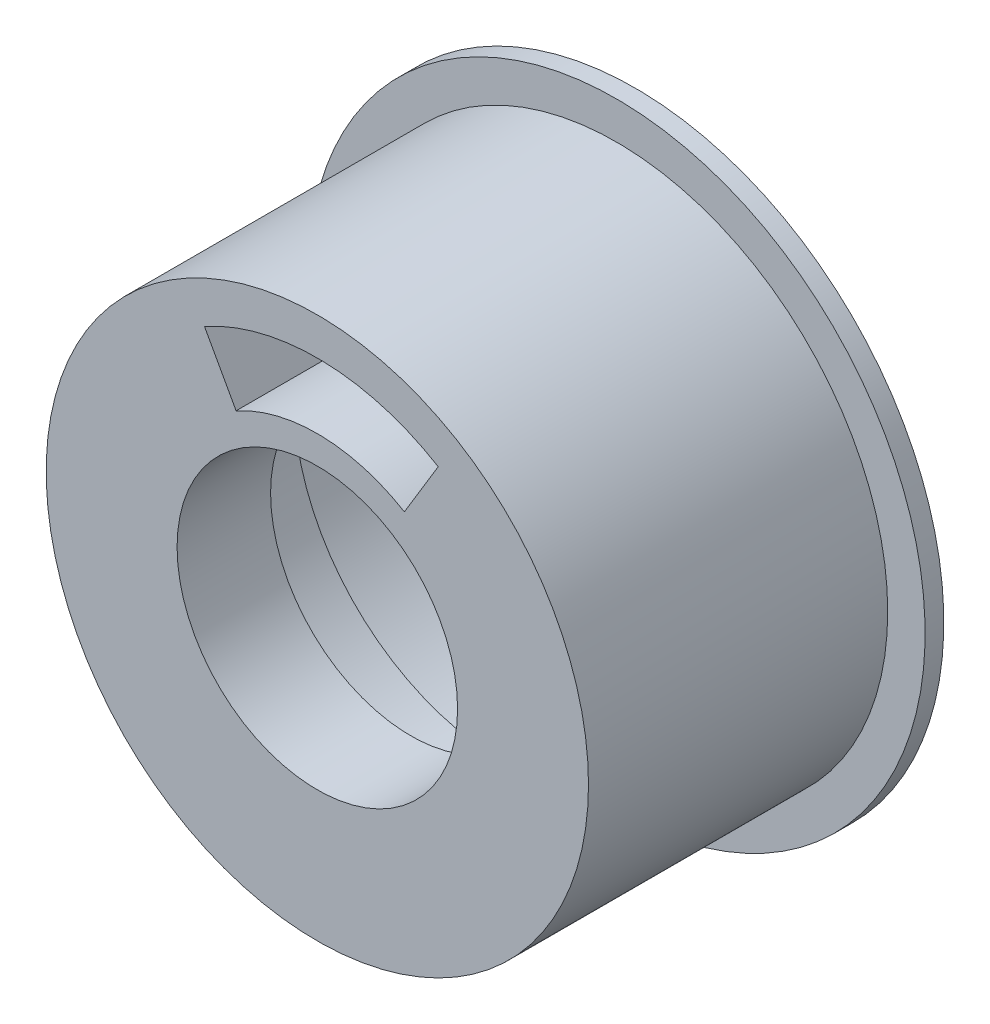
SolidWorks part; units mm, degrees
ref_plane "前视基准面" through (0, 0, 0) normal (0, 0, 1) x (1, 0, 0)
ref_plane "上视基准面" through (0, 0, 0) normal (0, 1, 0) x (1, 0, 0)
ref_plane "右视基准面" through (0, 0, 0) normal (1, 0, 0) x (0, 0, -1)
other "Configuration Table"
sketch "草图1" plane through (0, 0, 0) normal (0, 0, 1) x (1, 0, 0)
  circle A0 centre (0, 0) radius 26
  circle A1 centre (0, 0) radius 29
  dimension "D1" = 52
  dimension "D2" = 58
extrude "凸台-拉伸1" add sketch "草图1" along normal blind 12
sketch "草图2" plane through (0, 0, 12) normal (0, 0, 1) x (1, 0, 0)
  circle A0 centre (0, 0) radius 29
  circle A1 centre (0, 0) radius 22.5
  dimension "D1" = 45
extrude "凸台-拉伸2" add sketch "草图2" along normal blind 10
sketch "草图3" plane through (0, 0, 22) normal (0, 0, 1) x (1, 0, 0)
  circle A0 centre (0, 0) radius 29
  circle A1 centre (0, 0) radius 15
  dimension "D1" = 30
extrude "凸台-拉伸3" add sketch "草图3" along normal blind 10
sketch "草图4" plane through (0, 0, 32) normal (0, 0, 1) x (1, 0, 0)
  line L0 (-8.6897, 15.7635) -> (-12.069, 21.8938)
  line L1 (-12.069, 21.8938) -> (-8.6897, 15.7635)
  line L2 (9.3068, 15.4073) -> (12.9261, 21.399)
  arc A0 (9.3068, 15.4073) -> (-8.6897, 15.7635) centre (0, 0) ccw
  arc A1 (12.9261, 21.399) -> (-12.069, 21.8938) centre (0, 0) ccw
  dimension "D1" = 50
  dimension "D2" = 36
  dimension "D3" = 60
extrude "切除-拉伸1" cut sketch "草图4" against normal blind 33 contours L2 A1 L0 A0
sketch "草图5" plane through (0, 0, 0) normal (0, 0, -1) x (-1, 0, 0)
  circle A0 centre (0, 0) radius 26
  circle A1 centre (0, 0) radius 33
  dimension "D1" = 66
extrude "凸台-拉伸4" add sketch "草图5" along normal blind 2
